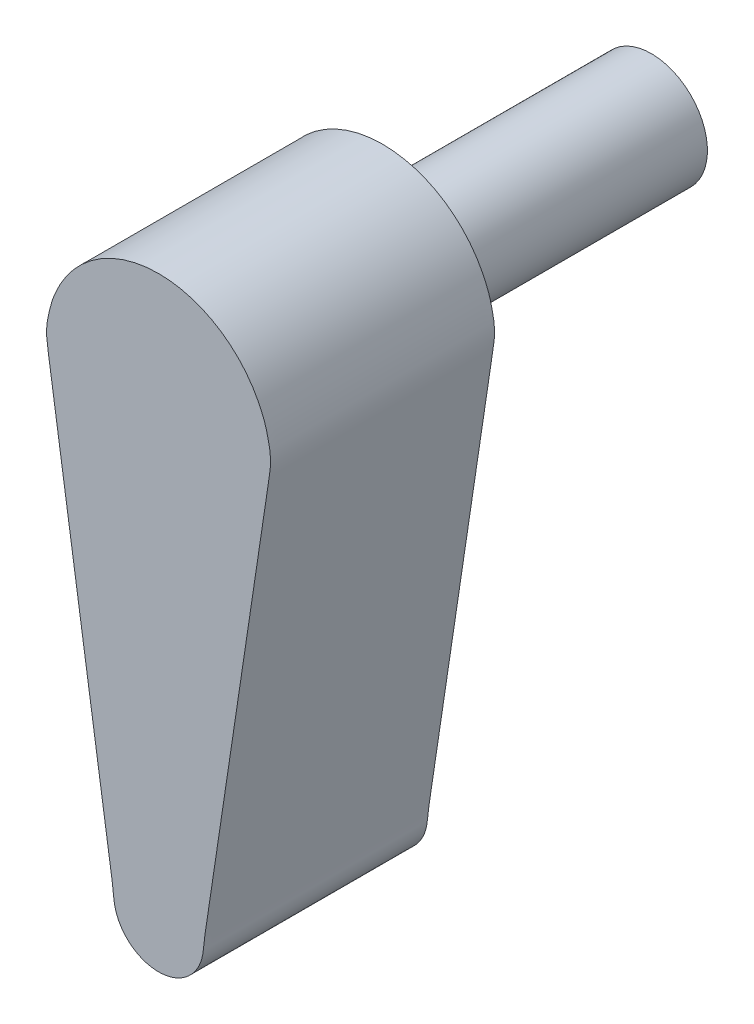
SolidWorks part; units mm, degrees
ref_plane "Front Plane" through (0, 0, 0) normal (0, 0, 1) x (1, 0, 0)
ref_plane "Top Plane" through (0, 0, 0) normal (0, 1, 0) x (1, 0, 0)
ref_plane "Right Plane" through (0, 0, 0) normal (1, 0, 0) x (0, 0, -1)
sketch "Sketch1" plane through (0, 0, 0) normal (0, 0, 1) x (1, 0, 0)
  line L0 (0, 13.5) -> (0, 0) construction
  line L1 (-2.5, 11) -> (-1, 1) construction
  line L2 (2.5, 11) -> (1, 1) construction
  arc A0 (-1, 1) -> (1, 1) centre (0, 1) ccw construction
  arc A1 (2.5, 11) -> (-2.5, 11) centre (0, 11) ccw construction
  spline S0 degree 3 poles (2.2312, 12.1278) (1.1729, 14.2214) (-1.1729, 14.2214) (-2.2312, 12.1278) (-2.2604, 12.0699) (-2.3144, 11.9519) (-2.3867, 11.769) (-2.4168, 11.6428) (-2.4319, 11.5797) (-2.4526, 11.4926) (-2.4942, 11.3183) (-2.506, 11.0401) (-2.4794, 10.8629) (-2.4662, 10.7744) (-2.4451, 10.6339) (-2.403, 10.353) (-2.3397, 9.9316) (-2.2976, 9.6507) (-2.2765, 9.5103) (-1.8641, 6.7603) (-1.4516, 4.0104) (-1.0391, 1.2605) (-1.0303, 1.2019) (-1.0127, 1.0848) (-1.001, 0.907) (-0.9795, 0.79) (-0.9637, 0.733) (-0.6282, -0.4778) (0.6282, -0.4778) (0.9637, 0.733) (0.9795, 0.79) (1.001, 0.907) (1.0127, 1.0848) (1.0303, 1.2019) (1.0391, 1.2605) (1.4516, 4.0104) (1.8641, 6.7603) (2.2765, 9.5103) (2.2976, 9.6507) (2.3397, 9.9316) (2.403, 10.353) (2.4451, 10.6339) (2.4662, 10.7744) (2.4794, 10.8629) (2.506, 11.0401) (2.4942, 11.3183) (2.4526, 11.4926) (2.4319, 11.5797) (2.4168, 11.6428) (2.3867, 11.769) (2.3144, 11.9519) (2.2604, 12.0699) (2.2312, 12.1278) (1.1729, 14.2214) (-1.1729, 14.2214) knots -0.006601 0 0 0 0.151391 0.151391 0.151391 0.157992 0.164592 0.171193 0.171193 0.171193 0.180308 0.189424 0.198539 0.198539 0.198539 0.212995 0.22745 0.241906 0.241906 0.241906 0.524922 0.524922 0.524922 0.530948 0.536975 0.543001 0.543001 0.543001 0.60839 0.60839 0.60839 0.614416 0.620443 0.626469 0.626469 0.626469 0.909485 0.909485 0.909485 0.923941 0.938396 0.952852 0.952852 0.952852 0.961967 0.971082 0.980198 0.980198 0.980198 0.986798 0.993399 1 1 1 1.151391 1.151391 1.151391 weights 1 0.634076 0.634076 1 1 1 1 1 1 1 1 1 1 1 1 1 1 1 1 1 1 1 1 1 1 1 1 0.511355 0.511355 1 1 1 1 1 1 1 1 1 1 1 1 1 1 1 1 1 1 1 1 1 1 1 1 0.634076 0.634076 only from (2.2312, 12.1278) to (2.2312, 12.1278)
  dimension "D2" = 5
  dimension "D3" = 2
  dimension "D1" = 13.5
extrude "Boss-Extrude1" add sketch "Sketch1" along normal blind 5
sketch "Sketch2" plane through (0, 0, 0) normal (0, 0, -1) x (-1, 0, 0)
  circle A0 centre (0, 11) radius 1.25
  dimension "D1" = 2.5
extrude "Boss-Extrude2" add sketch "Sketch2" along normal blind 6
